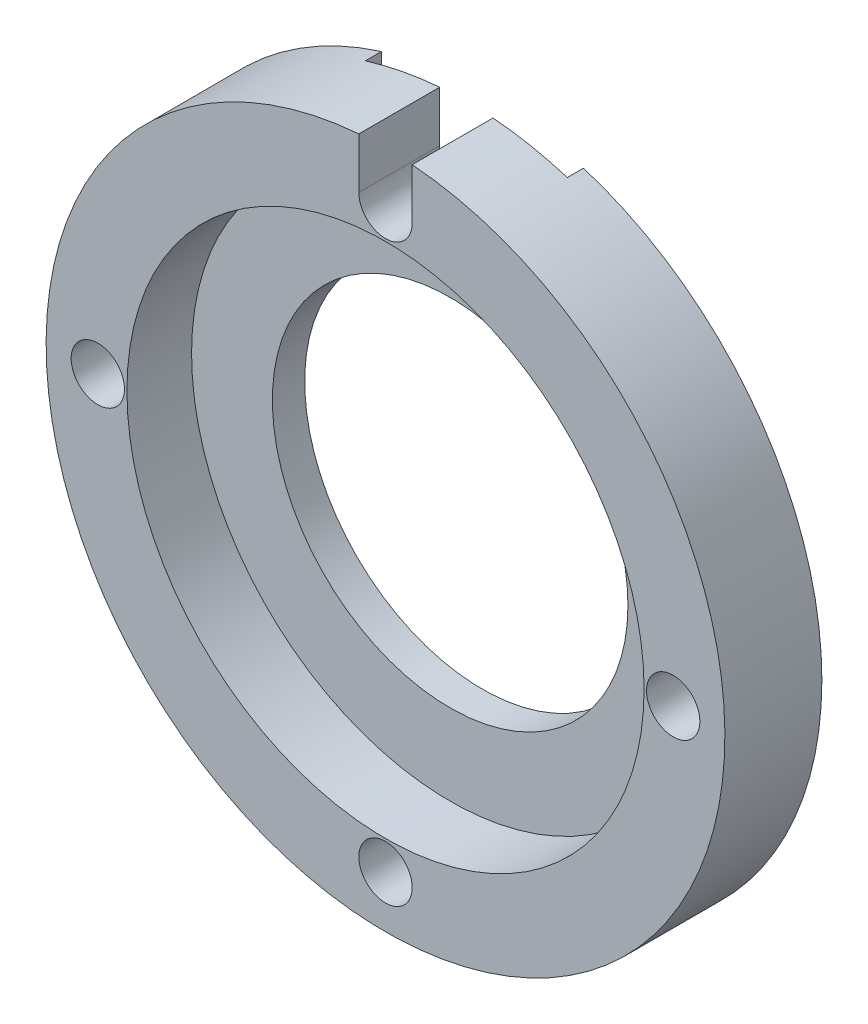
SolidWorks part; units mm, degrees
ref_plane "前视基准面" through (0, 0, 0) normal (0, 0, 1) x (1, 0, 0)
ref_plane "上视基准面" through (0, 0, 0) normal (0, 1, 0) x (1, 0, 0)
ref_plane "右视基准面" through (0, 0, 0) normal (1, 0, 0) x (0, 0, -1)
other "Configuration Table"
sketch "草图1" plane through (0, 0, 0) normal (0, 0, 1) x (1, 0, 0)
  circle A0 centre (0, 0) radius 21
  circle A1 centre (0, 0) radius 11
  dimension "D1" = 22
  dimension "D2" = 42
extrude "凸台-拉伸1" add sketch "草图1" along normal blind 2
sketch "草图2" plane through (0, 0, 2) normal (0, 0, 1) x (1, 0, 0)
  circle A0 centre (0, 0) radius 16
  circle A1 centre (0, 0) radius 21
  dimension "D1" = 32
  dimension "D2" = 42
extrude "凸台-拉伸2" add sketch "草图2" along normal blind 4
sketch "草图3" plane through (0, 0, 6) normal (0, 0, 1) x (1, 0, 0)
  circle A0 centre (17.8, 0) radius 1.65
  circle A1 centre (0, -17.8) radius 1.65
  circle A2 centre (-17.8, 0) radius 1.65
  circle A3 centre (0, 17.8) radius 1.65
  point P12 (0, 0)
  dimension "D1" = 3.3
  dimension "D2" = 17.8
  dimension "D3" = 4
extrude "切除-拉伸1" cut sketch "草图3" against normal up to next
sketch "草图4" plane through (0, 0, 6) normal (0, 0, 1) x (1, 0, 0)
  circle A0 centre (0, 17.8) radius 1.65 construction
  circle A1 centre (0, 17.8) radius 1.65
sketch "草图5" plane through (0, 0, 6) normal (0, 0, 1) x (1, 0, 0)
  line L0 (-1.65, 17.8) -> (-1.65, 20.9351)
  line L1 (1.65, 17.8) -> (1.65, 20.9351)
  circle A0 centre (0, 0) radius 21 construction
  arc A1 (1.65, 20.9351) -> (-1.65, 20.9351) centre (0, 0) ccw
  circle A2 centre (0, 17.8) radius 1.65 construction
  arc A3 (1.65, 17.8) -> (-1.65, 17.8) centre (0, 17.8) ccw
extrude "切除-拉伸2" cut sketch "草图5" against normal up to next
sketch "草图6" plane through (0, 0, 0) normal (0, 0, -1) x (-1, 0, 0)
  line L0 (-6.25, 9.0519) -> (-6.25, 20.0484)
  line L1 (6.25, 9.0519) -> (6.25, 20.0484)
  circle A0 centre (0, 0) radius 11 construction
  arc A1 (6.25, 9.0519) -> (-6.25, 9.0519) centre (0, 0) ccw
  arc A3 (6.25, 20.0484) -> (-6.25, 20.0484) centre (0, 0) ccw
extrude "切除-拉伸3" cut sketch "草图6" against normal blind 1
